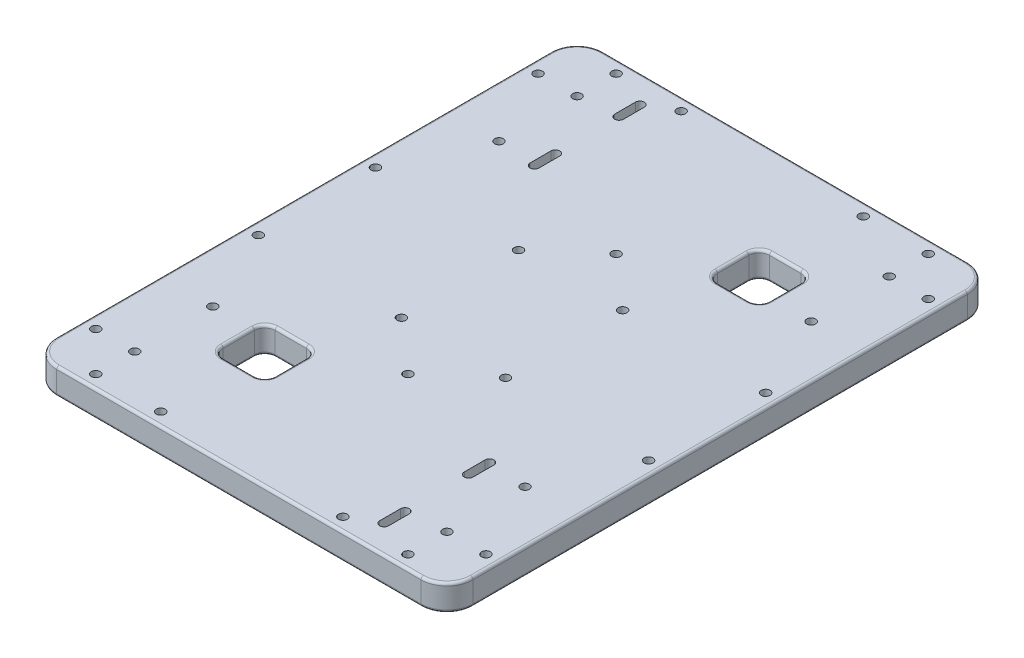
SolidWorks part; units mm, degrees
ref_plane "Front Plane" through (0, 0, 0) normal (0, 0, 1) x (1, 0, 0)
ref_plane "Top Plane" through (0, 0, 0) normal (0, 1, 0) x (1, 0, 0)
ref_plane "Right Plane" through (0, 0, 0) normal (1, 0, 0) x (0, 0, -1)
sketch "Sketch1" plane through (0, 0, 0) normal (0, 1, 0) x (1, 0, 0)
  line L1 (-80, 105) -> (80, 105)
  line L2 (-80, 105) -> (-80, -105)
  line L3 (-80, -105) -> (80, -105)
  line L4 (80, 105) -> (80, -105)
  line L5 (-80, 105) -> (80, -105) construction
  line L6 (-80, -105) -> (80, 105) construction
  point P0 (0, 0)
  dimension "D1" = 160
  dimension "D2" = 210
extrude "Boss-Extrude1" add sketch "Sketch1" along normal blind 10
sketch "Sketch2" plane through (0, 10, 0) normal (0, 1, 0) x (1, 0, 0)
  line L0 (0, 105) -> (0, -105) construction
  line L1 (80, 105) -> (-80, 105) construction
  line L2 (-80, -105) -> (80, -105) construction
  line L3 (-80, 0) -> (80, 0) construction
  line L4 (-80, 105) -> (-80, -105) construction
  line L5 (80, -105) -> (80, 105) construction
  line L6 (-75, 27.5) -> (-75, -27.5) construction
  line L7 (-70, 27.5) -> (-80, 27.5)
  line L8 (-70, 27.5) -> (-70, -27.5)
  line L9 (-70, -27.5) -> (-80, -27.5)
  line L10 (-80, 27.5) -> (-80, -27.5)
  line L11 (-70, 27.5) -> (-80, -27.5) construction
  line L12 (-70, -27.5) -> (-80, 27.5) construction
  line L13 (70, 27.5) -> (80, 27.5)
  line L14 (70, 27.5) -> (70, -27.5)
  line L15 (70, -27.5) -> (80, -27.5)
  line L16 (80, 27.5) -> (80, -27.5)
  line L17 (70, 27.5) -> (80, -27.5) construction
  line L18 (70, -27.5) -> (80, 27.5) construction
  line L19 (75, 27.5) -> (75, -27.5) construction
  circle A0 centre (-75, 22.5) radius 1.7
  circle A1 centre (-75, -22.5) radius 1.7
  circle A2 centre (75, 22.5) radius 1.7
  circle A3 centre (75, -22.5) radius 1.7
  point P12 (-75, 0)
  point P17 (75, 0)
  dimension "D5" = 3.4
  dimension "D6" = 3.4
  dimension "D7" = 5
  dimension "D8" = 5
  dimension "D9" = 3.4
  dimension "D10" = 5
  dimension "D11" = 3.4
  dimension "D12" = 5
  dimension "D1" = 10
  dimension "D2" = 55
  dimension "D3" = 55
  dimension "D4" = 10
extrude "Cut-Extrude1" cut sketch "Sketch2" against normal blind 10 contours A0 | A1 | A2 | A3
fillet "Fillet1" radius 10 4 edges at (80, 5, -105) (80, 5, 105) (-80, 5, 105) (-80, 5, -105)
sketch "Sketch3" plane through (0, 10, 0) normal (0, 1, 0) x (1, 0, 0)
  line L0 (0, 105) -> (0, -105) construction
  line L1 (70, 105) -> (-70, 105) construction
  line L2 (-70, -105) -> (70, -105) construction
  line L3 (-80, -70) -> (80, -70) construction
  line L4 (-80, 95) -> (-80, -95) construction
  line L5 (80, -95) -> (80, 95) construction
  line L6 (-80, 70) -> (80, 70) construction
  line L7 (45.1, -48.75) -> (45.1, -91.25) construction
  line L8 (20.1, -48.75) -> (50.1, -48.75)
  line L9 (20.1, -48.75) -> (20.1, -91.25)
  line L10 (20.1, -91.25) -> (50.1, -91.25)
  line L11 (50.1, -48.75) -> (50.1, -91.25)
  line L12 (20.1, -48.75) -> (50.1, -91.25) construction
  line L13 (20.1, -91.25) -> (50.1, -48.75) construction
  line L14 (-50.1, 91.25) -> (-20.1, 91.25)
  line L15 (-50.1, 91.25) -> (-50.1, 48.75)
  line L16 (-50.1, 48.75) -> (-20.1, 48.75)
  line L17 (-20.1, 91.25) -> (-20.1, 48.75)
  line L18 (-50.1, 91.25) -> (-20.1, 48.75) construction
  line L19 (-50.1, 48.75) -> (-20.1, 91.25) construction
  line L20 (-45.1, 91.25) -> (-45.1, 48.75) construction
  line L21 (45.1, -53.75) -> (45.1, -61.75) construction
  line L22 (45.1, -53.75) -> (45.1, -61.75) construction
  line L23 (46.8, -53.75) -> (46.8, -61.75)
  line L24 (43.4, -53.75) -> (43.4, -61.75)
  line L25 (45.1, -86.25) -> (45.1, -94.25) construction
  line L26 (46.8, -86.25) -> (46.8, -94.25)
  line L27 (43.4, -86.25) -> (43.4, -94.25)
  line L28 (-45.1, 53.75) -> (-45.1, 61.75) construction
  line L29 (-46.8, 53.75) -> (-46.8, 61.75)
  line L30 (-43.4, 53.75) -> (-43.4, 61.75)
  line L31 (-45.1, 86.25) -> (-45.1, 94.25) construction
  line L32 (-46.8, 86.25) -> (-46.8, 94.25)
  line L33 (-43.4, 86.25) -> (-43.4, 94.25)
  circle A0 centre (45.1, -53.75) radius 1.7
  circle A1 centre (45.1, -86.25) radius 1.7
  circle A2 centre (-45.1, 86.25) radius 1.7
  circle A3 centre (-45.1, 53.75) radius 1.7
  arc A6 (46.8, -53.75) -> (43.4, -53.75) centre (45.1, -53.75) ccw
  arc A7 (43.4, -61.75) -> (46.8, -61.75) centre (45.1, -61.75) ccw
  arc A8 (46.8, -86.25) -> (43.4, -86.25) centre (45.1, -86.25) ccw
  arc A9 (43.4, -94.25) -> (46.8, -94.25) centre (45.1, -94.25) ccw
  arc A10 (-46.8, 53.75) -> (-43.4, 53.75) centre (-45.1, 53.75) ccw
  arc A11 (-43.4, 61.75) -> (-46.8, 61.75) centre (-45.1, 61.75) ccw
  arc A12 (-46.8, 86.25) -> (-43.4, 86.25) centre (-45.1, 86.25) ccw
  arc A13 (-43.4, 94.25) -> (-46.8, 94.25) centre (-45.1, 94.25) ccw
  point P14 (35.1, -70)
  point P19 (-35.1, 70)
  point P36 (45.1, -57.75)
  point P43 (45.1, -90.25)
  point P49 (-45.1, 57.75)
  point P55 (-45.1, 90.25)
  dimension "D7" = 3.4
  dimension "D8" = 3.4
  dimension "D10" = 5
  dimension "D11" = 5
  dimension "D12" = 3.4
  dimension "D13" = 3.4
  dimension "D14" = 5
  dimension "D15" = 5
  dimension "D19" = 3.4
  dimension "D20" = 3.4
  dimension "D1" = 35
  dimension "D2" = 35
  dimension "D3" = 42.5
  dimension "D4" = 30
  dimension "D5" = 42.5
  dimension "D6" = 30
  dimension "D9" = 5
  dimension "D16" = 5
  dimension "D17" = 35.1
  dimension "D18" = 35.1
  dimension "D21" = 8
  dimension "D22" = 8
  dimension "D23" = 3.4
  dimension "D24" = 3.4
  dimension "D25" = 8
  dimension "D26" = 8
extrude "Cut-Extrude2" cut sketch "Sketch3" against normal blind 44.6 contours A0 | A3 | A2 | L33 A13 L32 A12 | L30 A11 L29 A10 | L27 A8 L26 A9 | L24 A7 L23 A6
sketch "Sketch4" plane through (0, 10, 0) normal (0, 1, 0) x (1, 0, 0)
  line L0 (-80, 0) -> (80, 0) construction
  line L1 (-80, 95) -> (-80, -95) construction
  line L2 (80, -95) -> (80, 95) construction
  line L3 (0, 105) -> (0, -105) construction
  line L4 (70, 105) -> (-70, 105) construction
  line L5 (-70, -105) -> (70, -105) construction
  line L6 (20, -27.5) -> (20, 27.5) construction
  line L7 (15, 27.5) -> (25, 27.5)
  line L8 (15, 27.5) -> (15, -27.5)
  line L9 (15, -27.5) -> (25, -27.5)
  line L10 (25, 27.5) -> (25, -27.5)
  line L11 (15, 27.5) -> (25, -27.5) construction
  line L12 (15, -27.5) -> (25, 27.5) construction
  line L13 (-25, 27.5) -> (-15, 27.5)
  line L14 (-25, 27.5) -> (-25, -27.5)
  line L15 (-25, -27.5) -> (-15, -27.5)
  line L16 (-15, 27.5) -> (-15, -27.5)
  line L17 (-25, 27.5) -> (-15, -27.5) construction
  line L18 (-25, -27.5) -> (-15, 27.5) construction
  line L19 (-20, 27.5) -> (-20, -27.5) construction
  circle A0 centre (20, 22.5) radius 1.7
  circle A1 centre (20, -22.5) radius 1.7
  circle A2 centre (-20, -22.5) radius 1.7
  circle A3 centre (-20, 22.5) radius 1.7
  point P12 (20, 0)
  point P17 (-20, 0)
  dimension "D7" = 3.4
  dimension "D8" = 3.4
  dimension "D9" = 3.4
  dimension "D10" = 3.4
  dimension "D11" = 5
  dimension "D12" = 5
  dimension "D13" = 5
  dimension "D14" = 5
  dimension "D1" = 10
  dimension "D2" = 10
  dimension "D3" = 55
  dimension "D4" = 55
  dimension "D5" = 15
  dimension "D6" = 15
extrude "Cut-Extrude3" cut sketch "Sketch4" against normal blind 44.6 contours A3 | A2 | A1 | A0
sketch "Sketch5" plane through (0, 10, 0) normal (0, 1, 0) x (1, 0, 0)
  line L0 (70, -95) -> (80, -95) construction
  line L1 (70, -95) -> (70, -105) construction
  line L2 (80, -95) -> (80, 95) construction
  line L3 (70, -95) -> (80, -95)
  line L4 (70, -95) -> (70, -80)
  line L5 (70, -80) -> (80, -80)
  line L6 (80, -95) -> (80, -80)
  line L7 (-70, -105) -> (70, -105) construction
  line L8 (70, -95) -> (55, -95)
  line L9 (70, -95) -> (70, -105)
  line L10 (70, -105) -> (55, -105)
  line L11 (55, -95) -> (55, -105)
  line L12 (60, -95) -> (60, -105) construction
  line L13 (70, -85) -> (80, -85) construction
  line L14 (0, 105) -> (0, -105) construction
  line L15 (70, 105) -> (-70, 105) construction
  line L16 (-70, -85) -> (-80, -85) construction
  line L17 (-60, -95) -> (-60, -105) construction
  line L18 (-70, -95) -> (-70, -105) construction
  line L19 (-70, -95) -> (-80, -95) construction
  line L20 (-55, -95) -> (-55, -105)
  line L21 (-70, -105) -> (-55, -105)
  line L22 (-70, -95) -> (-70, -105)
  line L23 (-70, -95) -> (-55, -95)
  line L24 (-80, -95) -> (-80, -80)
  line L25 (-70, -80) -> (-80, -80)
  line L26 (-70, -95) -> (-70, -80)
  line L27 (-70, -95) -> (-80, -95)
  line L28 (-80, 0) -> (80, 0) construction
  line L29 (-80, 95) -> (-80, -95) construction
  line L30 (-70, 95) -> (-80, 95) construction
  line L31 (-70, 95) -> (-70, 105) construction
  line L32 (-60, 95) -> (-60, 105) construction
  line L33 (-70, 85) -> (-80, 85) construction
  line L34 (70, 85) -> (80, 85) construction
  line L35 (60, 95) -> (60, 105) construction
  line L36 (70, 95) -> (70, 105) construction
  line L37 (70, 95) -> (80, 95) construction
  line L38 (-70, 95) -> (-80, 95)
  line L39 (-70, 95) -> (-70, 80)
  line L40 (-70, 80) -> (-80, 80)
  line L41 (-80, 95) -> (-80, 80)
  line L42 (-70, 95) -> (-55, 95)
  line L43 (-70, 95) -> (-70, 105)
  line L44 (-70, 105) -> (-55, 105)
  line L45 (-55, 95) -> (-55, 105)
  line L46 (55, 95) -> (55, 105)
  line L47 (70, 105) -> (55, 105)
  line L48 (70, 95) -> (70, 105)
  line L49 (70, 95) -> (55, 95)
  line L50 (80, 95) -> (80, 80)
  line L51 (70, 80) -> (80, 80)
  line L52 (70, 95) -> (70, 80)
  line L53 (70, 95) -> (80, 95)
  arc A0 (80, -95) -> (70, -105) centre (70, -95) cw
  circle A1 centre (60, -100) radius 1.7
  circle A2 centre (75, -85) radius 1.7
  circle A3 centre (-75, -85) radius 1.7
  circle A4 centre (-60, -100) radius 1.7
  arc A5 (-80, -95) -> (-70, -105) centre (-70, -95) ccw
  arc A6 (-80, 95) -> (-70, 105) centre (-70, 95) cw
  circle A7 centre (-60, 100) radius 1.7
  circle A8 centre (-75, 85) radius 1.7
  circle A9 centre (75, 85) radius 1.7
  circle A10 centre (60, 100) radius 1.7
  arc A11 (80, 95) -> (70, 105) centre (70, 95) ccw
  dimension "D1" = 15
  dimension "D3" = 3.4
  dimension "D4" = 3.4
  dimension "D2" = 15
  dimension "D5" = 5
  dimension "D6" = 5
extrude "Cut-Extrude4" cut sketch "Sketch5" against normal blind 32 contours A3 | A4 | A1 | A2 | A7 | A8 | A10 | A9
sketch "Sketch6" plane through (0, 0, 0) normal (0, -1, 0) x (1, 0, 0)
  line L0 (0, 105) -> (0, -105) construction
  line L1 (-70, 105) -> (70, 105) construction
  line L2 (70, -105) -> (-70, -105) construction
  line L3 (-80, 0) -> (80, 0) construction
  line L4 (-80, -95) -> (-80, 95) construction
  line L5 (80, 95) -> (80, -95) construction
  line L6 (0, 70) -> (60, 70) construction
  line L7 (0, 70) -> (-60, 70) construction
  line L8 (0, -70) -> (60, -70) construction
  line L9 (0, -70) -> (-60, -70) construction
  line L10 (-60, 70) -> (-60, 85) construction
  line L11 (-60, 70) -> (-60, 55) construction
  line L12 (60, 70) -> (60, 85) construction
  line L13 (60, 70) -> (60, 55) construction
  line L14 (-60, -70) -> (-60, -55) construction
  line L15 (-60, -70) -> (-60, -85) construction
  line L16 (60, -70) -> (60, -55) construction
  line L17 (60, -70) -> (60, -85) construction
  circle A0 centre (-60, 85) radius 1.7
  circle A1 centre (-60, 55) radius 1.7
  circle A2 centre (60, 55) radius 1.7
  circle A3 centre (60, 85) radius 1.7
  circle A4 centre (-60, -85) radius 1.7
  circle A5 centre (-60, -55) radius 1.7
  circle A6 centre (60, -55) radius 1.7
  circle A7 centre (60, -85) radius 1.7
  dimension "D15" = 3.4
  dimension "D16" = 3.4
  dimension "D17" = 3.4
  dimension "D18" = 3.4
  dimension "D19" = 3.4
  dimension "D20" = 3.4
  dimension "D21" = 3.4
  dimension "D22" = 3.4
  dimension "D1" = 60
  dimension "D2" = 60
  dimension "D3" = 60
  dimension "D4" = 60
  dimension "D5" = 70
  dimension "D6" = 70
  dimension "D7" = 15
  dimension "D8" = 15
  dimension "D9" = 15
  dimension "D10" = 15
  dimension "D11" = 15
  dimension "D12" = 15
  dimension "D13" = 15
  dimension "D14" = 15
extrude "Cut-Extrude5" cut sketch "Sketch6" against normal blind 35
sketch "Sketch7" plane through (0, 10, 0) normal (0, 1, 0) x (1, 0, 0)
  line L0 (0, 105) -> (0, -105) construction
  line L1 (70, 105) -> (-70, 105) construction
  line L2 (-70, -105) -> (70, -105) construction
  circle A0 centre (0, 40) radius 1.7
  circle A1 centre (0, -40) radius 1.7
  dimension "D1" = 3.4
  dimension "D2" = 3.4
  dimension "D4" = 40
  dimension "D3" = 40
extrude "Cut-Extrude6" cut sketch "Sketch7" against normal blind 42
sketch "Sketch8" plane through (0, 10, 0) normal (0, 1, 0) x (1, 0, 0)
  line L0 (0, -105) -> (0, 105) construction
  line L1 (-70, -105) -> (70, -105) construction
  line L2 (70, 105) -> (-70, 105) construction
  line L3 (80, -100) -> (-80, -100) construction
  line L4 (80, -95) -> (80, 95) construction
  line L5 (-80, 95) -> (-80, -95) construction
  line L6 (80, 100) -> (-80, 100) construction
  circle A0 centre (-35, -100) radius 1.7
  circle A1 centre (35, -100) radius 1.7
  circle A2 centre (35, 100) radius 1.7
  circle A3 centre (-35, 100) radius 1.7
  dimension "D3" = 3.4
  dimension "D4" = 3.4
  dimension "D5" = 35
  dimension "D6" = 35
  dimension "D7" = 3.4
  dimension "D8" = 3.4
  dimension "D9" = 35
  dimension "D10" = 35
  dimension "D1" = 5
  dimension "D2" = 5
extrude "Cut-Extrude7" cut sketch "Sketch8" against normal blind 42
fillet "Fillet2" radius 1 16 edges at (-77.0711, 0, -102.0711) (0, 0, -105) (77.0711, 0, -102.0711) (80, 0, 0) (77.0711, 0, 102.0711) (0, 0, 105) (-77.0711, 0, 102.0711) (-77.0711, 10, -102.0711) (0, 10, -105) (77.0711, 10, -102.0711) (80, 10, 0) (77.0711, 10, 102.0711) (0, 10, 105) (-77.0711, 10, 102.0711) (-80, 0, 0) (-80, 10, 0)
sketch "Sketch9" plane through (0, 10, 0) normal (0, 1, 0) x (1, 0, 0)
  line L0 (0, 105) -> (0, -105) construction
  line L1 (-70, 105) -> (70, 105) construction
  line L2 (70, -105) -> (-70, -105) construction
  line L4 (-45, -50) -> (-25, -50)
  line L5 (-45, -50) -> (-45, -70)
  line L6 (-45, -70) -> (-25, -70)
  line L7 (-25, -50) -> (-25, -70)
  line L12 (25, 70) -> (45, 70)
  line L13 (25, 70) -> (25, 50)
  line L14 (25, 50) -> (45, 50)
  line L15 (45, 70) -> (45, 50)
  dimension "D1" = 20
  dimension "D2" = 20
  dimension "D3" = 20
  dimension "D4" = 20
  dimension "D5" = 25
  dimension "D6" = 35
  dimension "D7" = 25
  dimension "D8" = 35
extrude "Cut-Extrude8" cut sketch "Sketch9" against normal blind 41
fillet "Fillet3" radius 4 8 edges at (25, 5, -50) (25, 5, -70) (45, 5, -70) (45, 5, -50) (-25, 5, 70) (-45, 5, 70) (-25, 5, 50) (-45, 5, 50)
fillet "Fillet4" radius 1 32 edges at (26.1716, 0, -68.8284) (35, 0, -70) (43.8284, 0, -68.8284) (45, 0, -60) (43.8284, 0, -51.1716) (35, 0, -50) (26.1716, 0, -51.1716) (26.1716, 10, -68.8284) (35, 10, -70) (43.8284, 10, -68.8284) (45, 10, -60) (43.8284, 10, -51.1716) (35, 10, -50) (26.1716, 10, -51.1716) (-43.8284, 0, 51.1716) (-35, 0, 50) (-26.1716, 0, 51.1716) (-25, 0, 60) (-26.1716, 0, 68.8284) (-35, 0, 70) (-43.8284, 0, 68.8284) (-43.8284, 10, 51.1716) (-35, 10, 50) (-26.1716, 10, 51.1716) (-25, 10, 60) (-26.1716, 10, 68.8284) (-35, 10, 70) (-43.8284, 10, 68.8284) (25, 0, -60) (25, 10, -60) (-45, 0, 60) (-45, 10, 60)
